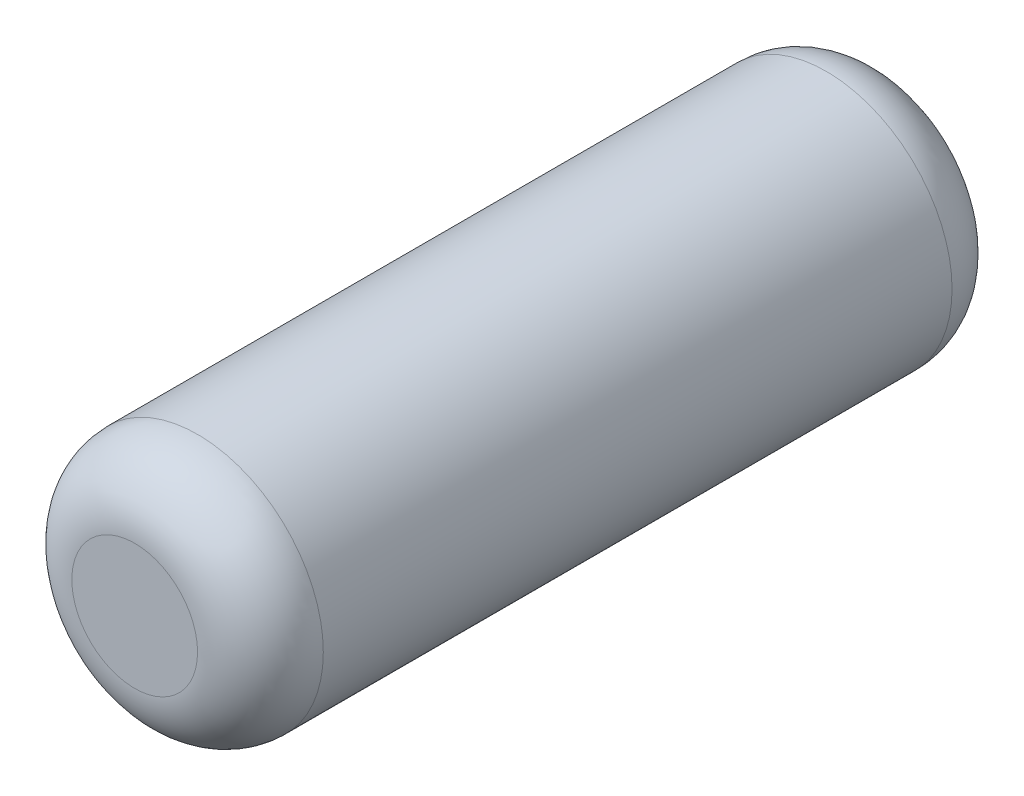
SolidWorks part; units mm, degrees
ref_plane "Front Plane" through (0, 0, 0) normal (0, 0, 1) x (1, 0, 0)
ref_plane "Top Plane" through (0, 0, 0) normal (0, 1, 0) x (1, 0, 0)
ref_plane "Right Plane" through (0, 0, 0) normal (1, 0, 0) x (0, 0, -1)
sketch "Sketch1" plane through (0, 0, 0) normal (0, 0, 1) x (1, 0, 0)
  circle A0 centre (0, 0) radius 50
  dimension "D1" = 100
extrude "Boss-Extrude1" add sketch "Sketch1" along normal mid plane 300
fillet "Fillet1" radius 25 2 edges at (50, 0, -150) (50, 0, 150)
